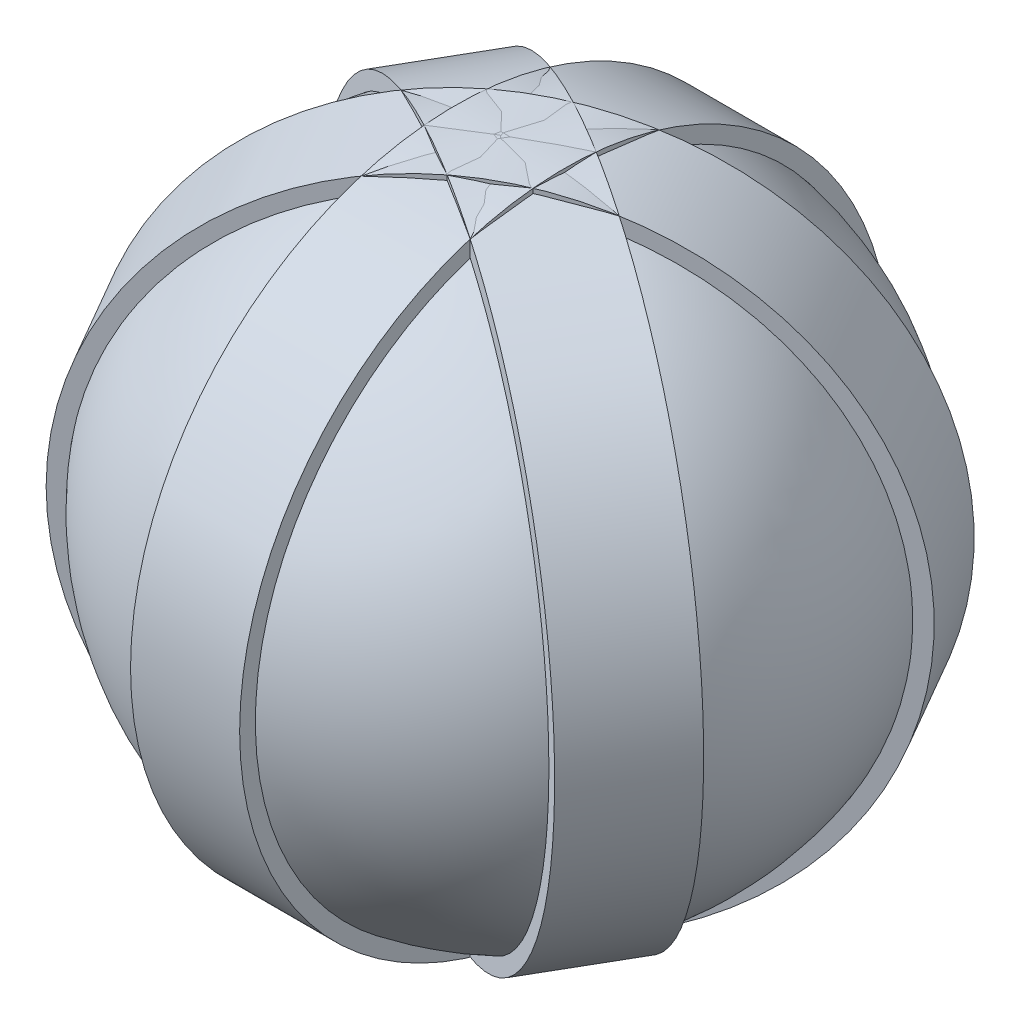
SolidWorks part; units mm, degrees
ref_plane "Plan de face" through (0, 0, 0) normal (0, 0, 1) x (1, 0, 0)
ref_plane "Plan de dessus" through (0, 0, 0) normal (0, 1, 0) x (1, 0, 0)
ref_plane "Plan de droite" through (0, 0, 0) normal (1, 0, 0) x (0, 0, -1)
sketch "Esquisse1" plane through (0, 0, 0) normal (0, 0, 1) x (1, 0, 0)
  line L0 (0, 0) -> (40, 0)
  arc A0 (0, 0) -> (40, 0) centre (20, 0) cw
  point P3 (20, 0)
  dimension "D1" = 20
revolve "Révolution1" add sketch "Esquisse1" angle 360 about L0
sketch "Esquisse2" plane through (0, 0, 0) normal (0, 0, 1) x (1, 0, 0)
  line L0 (20, 0) -> (20, 20) construction
  line L1 (16.527, 19.6962) -> (20, 0) construction
  line L2 (20, 0) -> (23.473, 19.6962) construction
  line L3 (16.527, 19.6962) -> (16.527, 20.6962)
  line L4 (16.527, 20.6962) -> (23.473, 20.6962)
  line L5 (23.473, 20.6962) -> (23.473, 19.6962)
  line L6 (0, 0) -> (40, 0) construction
  arc A0 (16.527, 19.6962) -> (23.473, 19.6962) centre (20, 0) cw
  circle A1 centre (20, 0) radius 20 construction
  dimension "D1" = 10
  dimension "D2" = 10
  dimension "D3" = 1
revolve "Révolution2" add sketch "Esquisse2" angle 360 about L6
sketch "Esquisse4" plane through (0, 0, 0) normal (0, 1, 0) x (1, 0, 0)
  line L0 (20, 20.6962) -> (20, -20.6962) construction
  line L1 (23.473, 20.6962) -> (16.527, 20.6962) construction
  line L2 (16.527, -20.6962) -> (23.473, -20.6962) construction
pattern_circular "Répétition circulaire3" count 3 every 60 about axis through (20, 0, 0) along (0, 1, 0) of bodies 102
